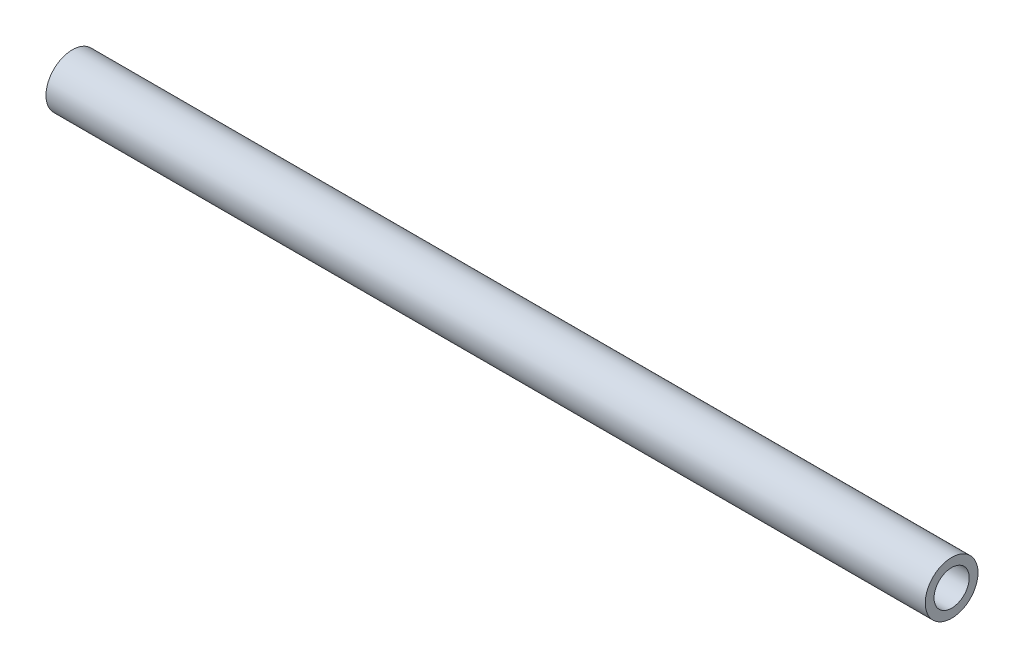
SolidWorks part; units mm, degrees
material "Perspex (TM) GS Acrylic Cast Sheet"
ref_plane "Front Plane" through (0, 0, 0) normal (0, 0, 1) x (1, 0, 0)
ref_plane "Top Plane" through (0, 0, 0) normal (0, 1, 0) x (1, 0, 0)
ref_plane "Right Plane" through (0, 0, 0) normal (1, 0, 0) x (0, 0, -1)
sketch "Sketch1" plane through (0, 0, 0) normal (1, 0, 0) x (0, 0, -1)
  circle A0 centre (0, 0) radius 3
  circle A1 centre (0, 0) radius 2
  dimension "D1" = 6
  dimension "D2" = 4
extrude "Boss-Extrude1" add sketch "Sketch1" along normal mid plane 100
